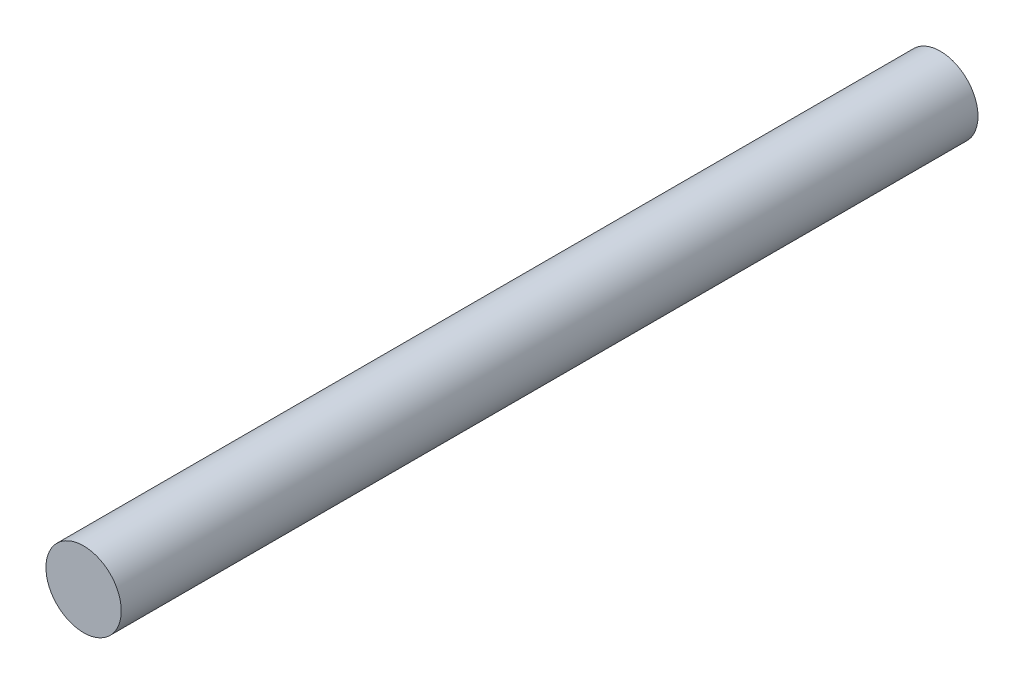
SolidWorks part; units mm, degrees
ref_plane "Front Plane" through (0, 0, 0) normal (0, 0, 1) x (1, 0, 0)
ref_plane "Top Plane" through (0, 0, 0) normal (0, 1, 0) x (1, 0, 0)
ref_plane "Right Plane" through (0, 0, 0) normal (1, 0, 0) x (0, 0, -1)
sketch "Sketch1" plane through (0, 0, 0) normal (0, 0, 1) x (1, 0, 0)
  circle A0 centre (0, 0) radius 0.8
extrude "Boss-Extrude1" add sketch "Sketch1" along normal blind 18.2
